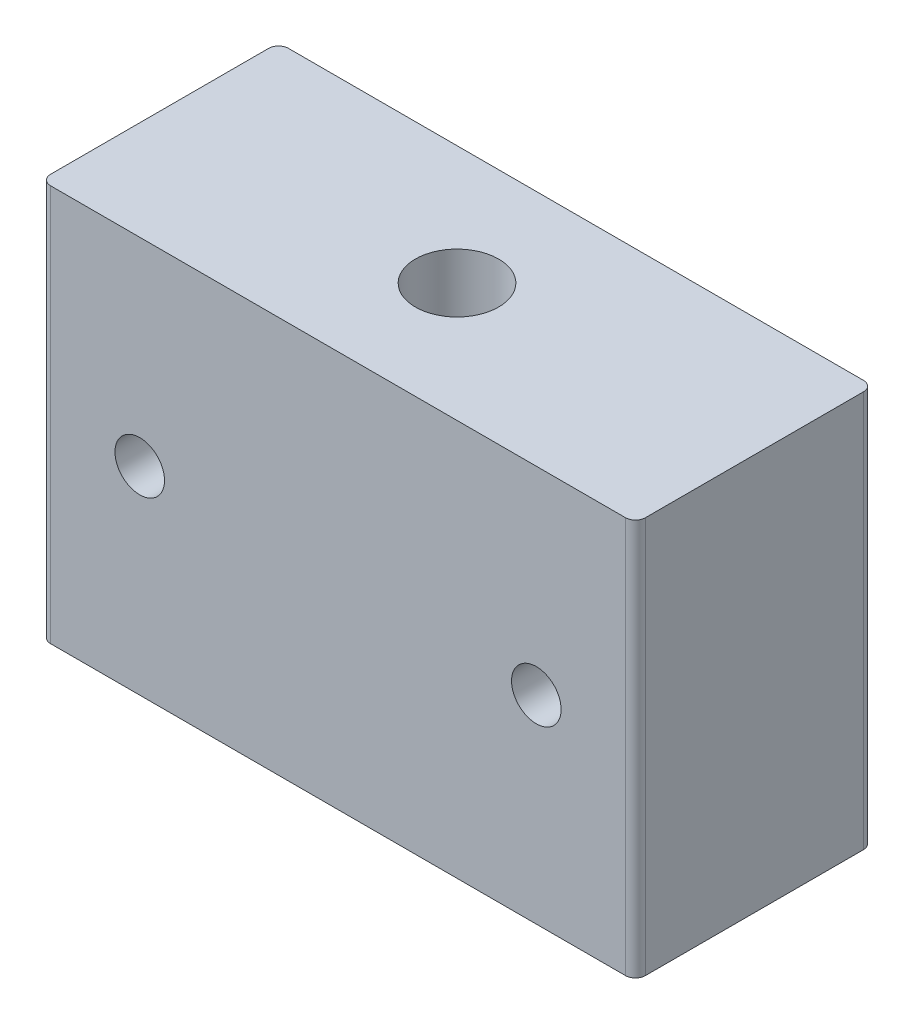
SolidWorks part; units mm, degrees
material "AISI 1045 Steel, cold drawn"
ref_plane "Front Plane" through (0, 0, 0) normal (0, 0, 1) x (1, 0, 0)
ref_plane "Top Plane" through (0, 0, 0) normal (0, 1, 0) x (1, 0, 0)
ref_plane "Right Plane" through (0, 0, 0) normal (1, 0, 0) x (0, 0, -1)
sketch "Sketch1" plane through (0, 0, 0) normal (0, 1, 0) x (1, 0, 0)
  line L1 (15, -6) -> (-15, -6)
  line L2 (15, -6) -> (15, 6)
  line L3 (15, 6) -> (-15, 6)
  line L4 (-15, -6) -> (-15, 6)
  line L5 (15, -6) -> (-15, 6) construction
  line L6 (15, 6) -> (-15, -6) construction
  point P0 (0, 0)
  dimension "D1" = 12
  dimension "D2" = 30
extrude "Boss-Extrude1" add sketch "Sketch1" along normal blind 20
hole_wizard "Tap Drill for M5x0.8 Tap1" positions "Sketch2" profile "Sketch3" hole size "M5x0.8" standard "ANSI Metric" end condition through all
sketch "Sketch2" plane through (0, 0, 0) normal (0, -1, 0) x (-1, 0, 0)
  point P0 (0, 0)
sketch "Sketch3" plane through (0, 0, 0) normal (1, 0, 0) x (0, 0, -1)
  line L0 (0, 0) -> (0, 20)
  line L1 (0, 20) -> (2.1, 20)
  line L2 (2.1, 20) -> (2.1, 0)
  line L5 (2.1, 0) -> (0, 0)
  line L11 (0, -6.35) -> (0, 107.95) construction
  dimension "Thru Hole Dia." = 4.2
  dimension "Thru Hole Depth" = 20
hole_wizard "Tap Drill for M3x0.5 Tap1" positions "Sketch4" profile "Sketch5" hole size "M3x0.5" standard "ANSI Metric" end condition through all
sketch "Sketch4" plane through (0, 0, 6) normal (0, 0, 1) x (1, 0, 0)
  line L0 (-10, 10) -> (10, 10) construction
  line L2 (-15, 20) -> (-15, 0) construction
  point P0 (-10, 10)
  point P2 (10, 10)
  point P7 (0, 10)
  point P11 (-15, 10)
  dimension "D1" = 20
sketch "Sketch5" plane through (-10, 10, 6) normal (1, 0, 0) x (0, -1, 0)
  line L0 (0, 0) -> (0, 12)
  line L1 (0, 12) -> (1.25, 12)
  line L2 (1.25, 12) -> (1.25, 0)
  line L5 (1.25, 0) -> (0, 0)
  line L11 (0, -6.35) -> (0, 107.95) construction
  dimension "Thru Hole Dia." = 2.5
  dimension "Thru Hole Depth" = 12
fillet "Fillet1" radius 0.5 4 edges at (-15, 10, -6) (15, 10, -6) (15, 10, 6) (-15, 10, 6)
